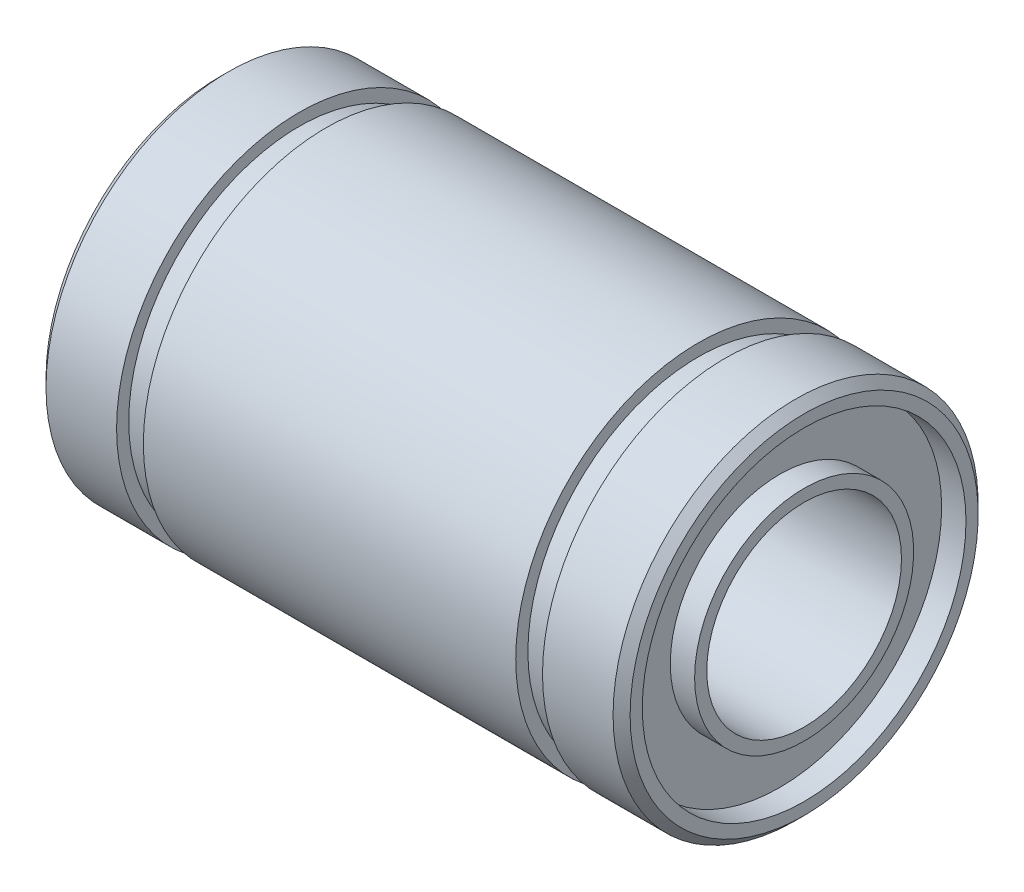
SolidWorks part; units mm, degrees
material "1060 Alloy"
ref_plane "Front Plane" through (0, 0, 0) normal (0, 0, 1) x (1, 0, 0)
ref_plane "Top Plane" through (0, 0, 0) normal (0, 1, 0) x (1, 0, 0)
ref_plane "Right Plane" through (0, 0, 0) normal (1, 0, 0) x (0, 0, -1)
sketch "Sketch1" plane through (0, 0, 0) normal (0, 0, 1) x (1, 0, 0)
  line L0 (-45.6895, 0) -> (45.6895, 0) construction
  line L1 (-11.65, 7.5) -> (-8.75, 7.5)
  line L2 (-8.75, 7.5) -> (-8.75, 7)
  line L3 (-8.75, 7) -> (-7.65, 7)
  line L4 (-7.65, 7) -> (-7.65, 7.5)
  line L5 (-7.65, 7.5) -> (7.65, 7.5)
  line L6 (0, 45.6895) -> (0, -45.6895) construction
  line L7 (-11.65, 7.5) -> (-12, 7.15)
  line L8 (-12, 7.15) -> (-12, 6.65)
  line L9 (-12, 6.65) -> (-11, 6.65)
  line L10 (-11, 6.65) -> (-11, 4.5)
  line L11 (-11, 4.5) -> (-12, 4.5)
  line L12 (-12, 4.5) -> (-12, 4)
  line L13 (-12, 4) -> (12, 4)
  line L14 (12, 4.5) -> (12, 4)
  line L15 (11, 4.5) -> (12, 4.5)
  line L16 (11, 6.65) -> (11, 4.5)
  line L17 (12, 6.65) -> (11, 6.65)
  line L18 (12, 7.15) -> (12, 6.65)
  line L19 (11.65, 7.5) -> (12, 7.15)
  line L20 (7.65, 7) -> (7.65, 7.5)
  line L21 (8.75, 7) -> (7.65, 7)
  line L22 (8.75, 7.5) -> (8.75, 7)
  line L23 (11.65, 7.5) -> (8.75, 7.5)
  point P19 (0, 4)
  point P26 (0, 7.5)
  dimension "D1" = 45
  dimension "D2" = 0.5
  dimension "L" = 24
  dimension "B" = 17.5
  dimension "W" = 1.1
  dimension "D" = 7.5
  dimension "D_1" = 7.15
  dimension "D3" = 0.5
  dimension "dr" = 4
  dimension "D4" = 0.5
  dimension "D5" = 1
revolve "Revolve1" add sketch "Sketch1" angle 360 about L0
equation "\"D\"=15"
equation "\"D1\"=14.3"
equation "\"dr\"=8"
equation "\"L\"=24"
equation "\"B\"=17.5"
equation "\"W\"=1.1"
equation "\"L@Sketch1\"= \"L\""
equation "\"B@Sketch1\"= \"B\""
equation "\"W@Sketch1\"= \"W\""
equation "\"dr@Sketch1\"= \"dr\" * 0.5"
equation "\"D@Sketch1\" = \"D\" * 0.5"
equation "\"D_1@Sketch1\" = \"D1\" * 0.5"
